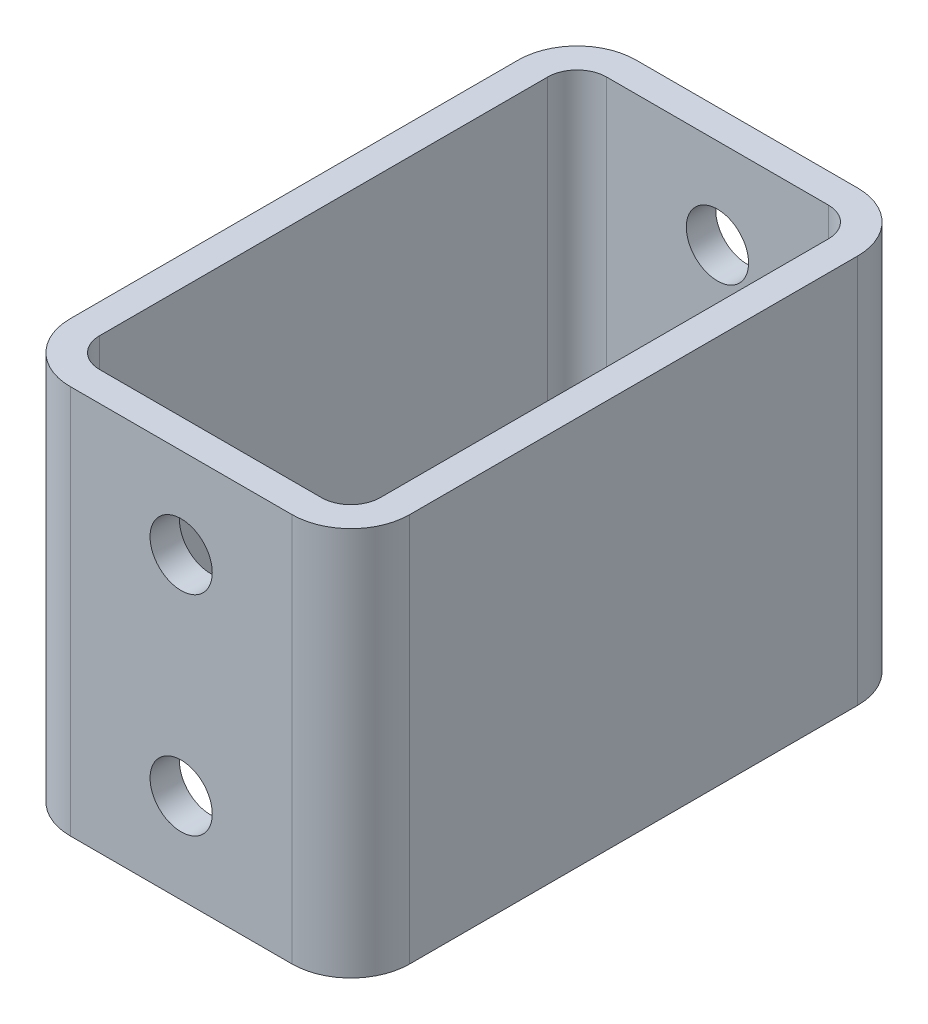
SolidWorks part; units mm, degrees
ref_plane "Front Plane" through (0, 0, 0) normal (0, 0, 1) x (1, 0, 0)
ref_plane "Top Plane" through (0, 0, 0) normal (0, 1, 0) x (1, 0, 0)
ref_plane "Right Plane" through (0, 0, 0) normal (1, 0, 0) x (0, 0, -1)
sketch3d "3DSketch1"
  line L0 (0, 0, 0) -> (0, 34.4, 0)
  dimension "D1" = 34.4
other "Rectangular tube - configured 50 X 30 X 2.6(1)"
ref_plane "Plane1" through (0, 0, 0) normal (0, 1, 0) x (1, 0, 0)
sketch "Sketch13" plane through (0, 0, 0) normal (0, 1, 0) x (1, 0, 0)
  line L0 (-9.8, -22.4) -> (9.8, -22.4)
  line L1 (-12.4, -19.8) -> (-12.4, 19.8)
  line L2 (9.8, 22.4) -> (-9.8, 22.4)
  line L3 (12.4, 19.8) -> (12.4, -19.8)
  line L4 (-9.8, -25) -> (9.8, -25)
  line L5 (-15, -19.8) -> (-15, 19.8)
  line L6 (9.8, 25) -> (-9.8, 25)
  line L7 (15, 19.8) -> (15, -19.8)
  arc A0 (15, 19.8) -> (9.8, 25) centre (9.8, 19.8) ccw
  arc A1 (9.8, -25) -> (15, -19.8) centre (9.8, -19.8) ccw
  arc A2 (-15, -19.8) -> (-9.8, -25) centre (-9.8, -19.8) ccw
  arc A3 (-9.8, 25) -> (-15, 19.8) centre (-9.8, 19.8) ccw
  arc A4 (-9.8, 22.4) -> (-12.4, 19.8) centre (-9.8, 19.8) ccw
  arc A5 (12.4, 19.8) -> (9.8, 22.4) centre (9.8, 19.8) ccw
  arc A6 (9.8, -22.4) -> (12.4, -19.8) centre (9.8, -19.8) ccw
  arc A7 (-12.4, -19.8) -> (-9.8, -22.4) centre (-9.8, -19.8) ccw
  point P0 (0, 25)
  point P1 (15, 0)
  point P2 (0, -25)
  point P3 (-15, 0)
  point P4 (-15, 25)
  point P5 (15, 25)
  point P6 (15, -25)
  point P7 (-15, -25)
  point P8 (0, 0)
  point P33 (0, 0)
  dimension "D1" = 5.2
  dimension "Thickness" = 2.6
  dimension "V_leg" = 50
  dimension "H_leg" = 30
sketch "Sketch14" plane through (0, 0, 25) normal (0, 0, 1) x (1, 0, 0)
  line L0 (-9.8, 26.435) -> (0, 26.435) construction
  line L1 (-9.8, 34.4) -> (-9.8, 0) construction
  line L2 (9.8, 7.965) -> (0, 7.965) construction
  line L3 (9.8, 34.4) -> (9.8, 0) construction
  line L4 (-9.8, 34.4) -> (9.8, 34.4) construction
  line L6 (0, 34.4) -> (0, 0) construction
  point P10 (0, 17.2)
  dimension "D1" = 18.47
  dimension "D2" = 9.235
hole_wizard "M5 Clearance Hole1" positions "3DSketch2" profile "Sketch15" hole size "M5" standard "ISO" end condition through all
sketch3d "3DSketch2"
  point P0 (0, 26.435, 25)
  point P3 (0, 7.965, 25)
sketch "Sketch15" plane through (0, 26.435, 25) normal (1, 0, 0) x (0, -1, 0)
  line L0 (0, 0) -> (0, 50)
  line L1 (0, 50) -> (2.75, 50)
  line L2 (2.75, 50) -> (2.75, 0)
  line L5 (2.75, 0) -> (0, 0)
  line L11 (0, -6.35) -> (0, 107.95) construction
  dimension "Thru Hole Dia." = 5.5
  dimension "Thru Hole Depth" = 50
